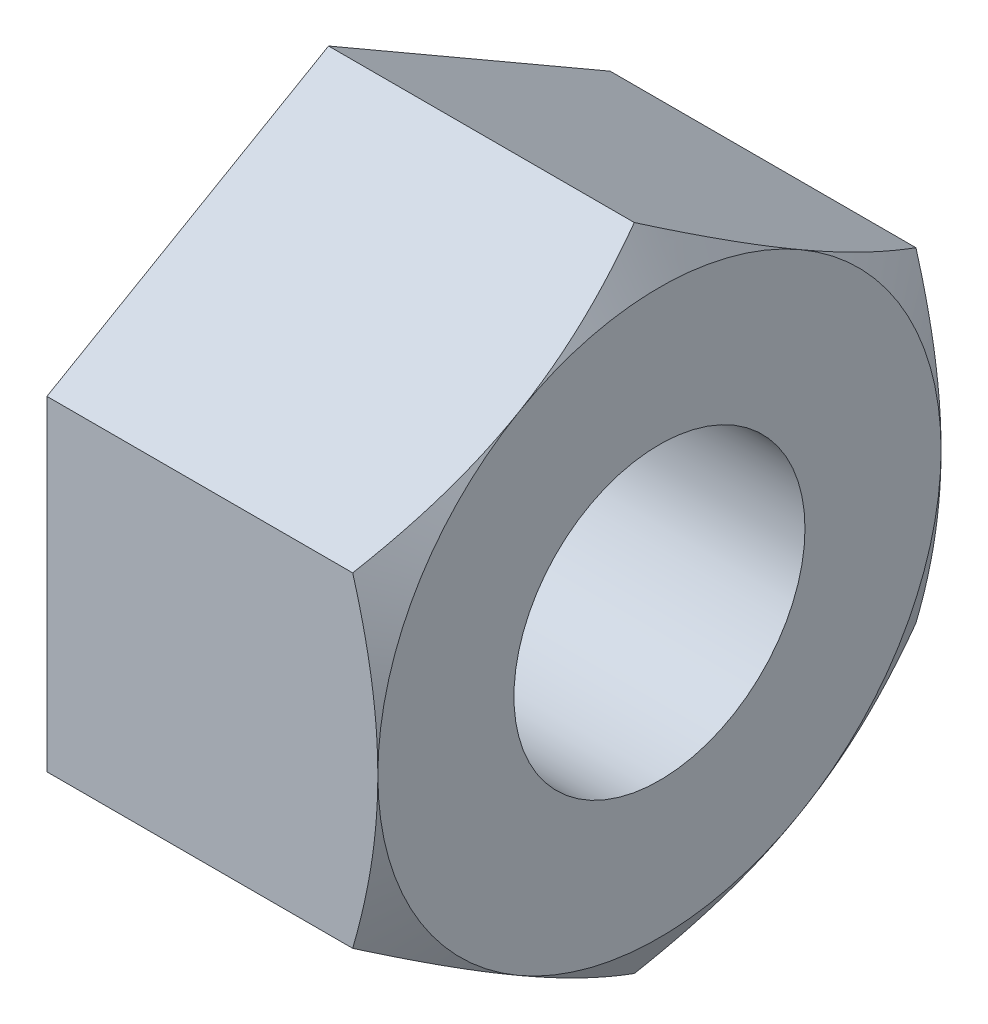
SolidWorks part; units mm, degrees
ref_plane "Front Plane" through (0, 0, 0) normal (0, 0, 1) x (1, 0, 0)
ref_plane "Top Plane" through (0, 0, 0) normal (0, 1, 0) x (1, 0, 0)
ref_plane "Right Plane" through (0, 0, 0) normal (1, 0, 0) x (0, 0, -1)
sketch "Sketch1" plane through (0, 0, 0) normal (1, 0, 0) x (0, 0, -1)
  line L1 (0, 4.6188) -> (-4, 2.3094)
  line L2 (-4, 2.3094) -> (-4, -2.3094)
  line L3 (-4, -2.3094) -> (0, -4.6188)
  line L4 (0, -4.6188) -> (4, -2.3094)
  line L5 (4, -2.3094) -> (4, 2.3094)
  line L6 (4, 2.3094) -> (0, 4.6188)
  circle A0 centre (0, 0) radius 4 construction
  dimension "FIX_1" = 8
extrude "Boss-Extrude1" add sketch "Sketch1" against normal blind 4.7
sketch "Sketch2" plane through (0, 0, 0) normal (0, 0, 1) x (1, 0, 0)
  line L5 (0, 4) -> (-0.3573, 4.6188)
  line L6 (0, 4.6188) -> (0, 2.3094) construction
  line L7 (-0.3573, 4.6188) -> (0, 4.6188)
  line L8 (0, 4.6188) -> (0, 4)
  line L9 (-0.3573, 0) -> (0, 0) construction
  dimension "FIX_3" = 30
  dimension "FIX_4" = 8
revolve "Cut-Revolve1" cut sketch "Sketch2" angle 360 about L9
hole_wizard "Tap1" positions "Sketch4" profile "Sketch3" hole size "M2x0.4" standard "JIS" end condition through all
sketch "Sketch4" plane through (0, 0, 0) normal (1, 0, 0) x (0, 0, -1)
  point P0 (0, 0)
cosmetic thread "Thread301" parameters "NFIX_1"=5
sketch "Sketch3" plane through (0, 0, 0) normal (0, 1, 0) x (0, 0, -1)
  line L0 (0, 0) -> (0, 4.7)
  line L1 (0, 4.7) -> (2.067, 4.7)
  line L2 (2.067, 4.7) -> (2.067, 0)
  line L5 (2.067, 0) -> (0, 0)
  line L11 (0, -6.35) -> (0, 107.95) construction
  dimension "FIX_6" = 4.134
  dimension "Thru Hole Depth" = 4.7
